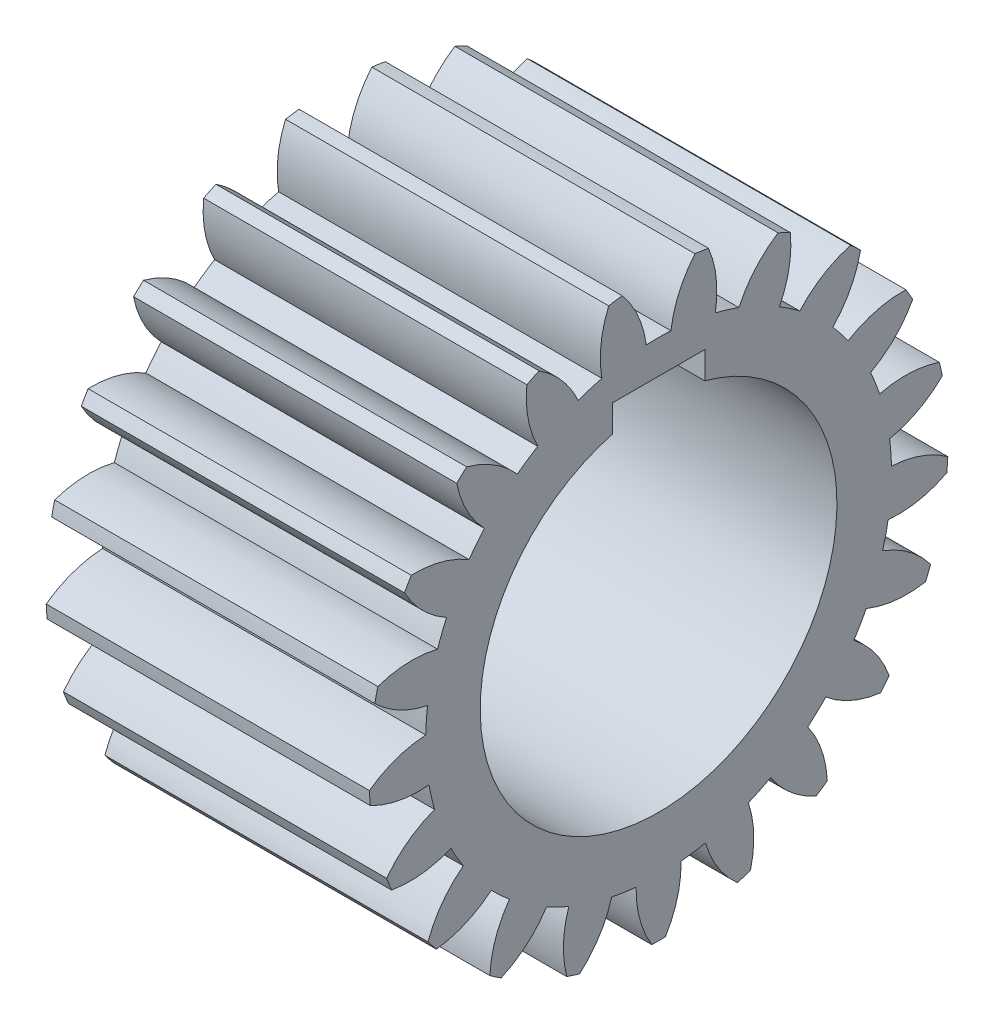
SolidWorks part; units mm, degrees
ref_plane "Plan de face" through (0, 0, 0) normal (0, 0, 1) x (1, 0, 0)
ref_plane "Plan de dessus" through (0, 0, 0) normal (0, 1, 0) x (1, 0, 0)
ref_plane "Plan de droite" through (0, 0, 0) normal (1, 0, 0) x (0, 0, -1)
ref_plane "Plan1" through (40.8214, 0, 0) normal (1, 0, 0) x (0, 0, -1)
sketch "Esquisse1" plane through (40.8214, 0, 0) normal (1, 0, 0) x (0, 0, -1)
  line L0 (-11, 30.2135) -> (11, 30.2135)
  line L1 (11, 30.2135) -> (11, 23.7653)
  line L2 (-11, 23.7653) -> (-11, 30.2135)
  arc A0 (11, 23.7653) -> (-11, 23.7653) centre (0, -17.2865) cw
  arc A1 (-67.6125, -3.5185) -> (-55.0464, -10.2132) centre (-49.9632, 14.4688) ccw
  arc A2 (-55.0464, -10.2132) -> (-55.4858, -16.0765) centre (0, -17.2865) ccw
  arc A3 (-55.4858, -16.0765) -> (-68.9093, -20.8235) centre (-54.138, -41.2404) ccw
  arc A4 (-68.9093, -20.8235) -> (-68.6668, -24.0593) centre (0, -17.2865) ccw
  arc A5 (-68.6668, -24.0593) -> (-54.6857, -26.7527) centre (-57.1035, -1.6689) ccw
  arc A6 (-54.6857, -26.7527) -> (-53.3774, -32.485) centre (0, -17.2865) ccw
  arc A7 (-53.3774, -32.485) -> (-64.8053, -40.9778) centre (-44.6723, -56.1337) ccw
  arc A8 (-64.8053, -40.9778) -> (-63.6198, -43.9983) centre (0, -17.2865) ccw
  arc A9 (-63.6198, -43.9983) -> (-49.466, -42.451) centre (-59.1699, -19.1943) ccw
  arc A10 (-49.466, -42.451) -> (-46.5261, -47.543) centre (0, -17.2865) ccw
  arc A11 (-46.5261, -47.543) -> (-54.943, -59.0269) centre (-31.2372, -67.5752) ccw
  arc A12 (-54.943, -59.0269) -> (-52.9199, -61.5638) centre (0, -17.2865) ccw
  arc A13 (-52.9199, -61.5638) -> (-39.851, -55.9134) centre (-55.9788, -36.5502) ccw
  arc A14 (-39.851, -55.9134) -> (-35.5408, -59.9126) centre (0, -17.2865) ccw
  arc A15 (-35.5408, -59.9126) -> (-40.1989, -73.3672) centre (-15.0266, -74.5483) ccw
  arc A16 (-40.1989, -73.3672) -> (-37.5178, -75.1951) centre (0, -17.2865) ccw
  arc A17 (-37.5178, -75.1951) -> (-26.695, -65.9436) centre (-47.8137, -52.1944) ccw
  arc A18 (-26.695, -65.9436) -> (-21.3976, -68.4947) centre (0, -17.2865) ccw
  arc A19 (-21.3976, -68.4947) -> (-21.8828, -82.7245) centre (2.5193, -76.4335) ccw
  arc A20 (-21.8828, -82.7245) -> (-18.7821, -83.681) centre (0, -17.2865) ccw
  arc A21 (-18.7821, -83.681) -> (-11.1671, -71.6504) centre (-35.4002, -64.7369) ccw
  arc A22 (-11.1671, -71.6504) -> (-5.3531, -72.5267) centre (0, -17.2865) ccw
  arc A23 (-5.3531, -72.5267) -> (-1.6224, -86.2674) centre (19.8412, -73.0632) ccw
  arc A24 (-1.6224, -86.2674) -> (1.6224, -86.2674) centre (0, -17.2865) ccw
  arc A25 (1.6224, -86.2674) -> (5.3531, -72.5267) centre (-19.8412, -73.0632) ccw
  arc A26 (5.3531, -72.5267) -> (11.1671, -71.6504) centre (0, -17.2865) ccw
  arc A27 (11.1671, -71.6504) -> (18.7821, -83.681) centre (35.4002, -64.7369) ccw
  arc A28 (18.7821, -83.681) -> (21.8828, -82.7245) centre (0, -17.2865) ccw
  arc A29 (21.8828, -82.7245) -> (21.3976, -68.4947) centre (-2.5193, -76.4335) ccw
  arc A30 (21.3976, -68.4947) -> (26.695, -65.9436) centre (0, -17.2865) ccw
  arc A31 (26.695, -65.9436) -> (37.5178, -75.1951) centre (47.8137, -52.1944) ccw
  arc A32 (37.5178, -75.1951) -> (40.1989, -73.3672) centre (0, -17.2865) ccw
  arc A33 (40.1989, -73.3672) -> (35.5408, -59.9126) centre (15.0266, -74.5483) ccw
  arc A34 (35.5408, -59.9126) -> (39.851, -55.9134) centre (0, -17.2865) ccw
  arc A35 (39.851, -55.9134) -> (52.9199, -61.5638) centre (55.9788, -36.5502) ccw
  arc A36 (52.9199, -61.5638) -> (54.943, -59.0269) centre (0, -17.2865) ccw
  arc A37 (54.943, -59.0269) -> (46.5261, -47.543) centre (31.2372, -67.5752) ccw
  arc A38 (46.5261, -47.543) -> (49.466, -42.451) centre (0, -17.2865) ccw
  arc A39 (49.466, -42.451) -> (63.6198, -43.9983) centre (59.1699, -19.1943) ccw
  arc A40 (63.6198, -43.9983) -> (64.8053, -40.9778) centre (0, -17.2865) ccw
  arc A41 (64.8053, -40.9778) -> (53.3774, -32.485) centre (44.6723, -56.1337) ccw
  arc A42 (53.3774, -32.485) -> (54.6857, -26.7527) centre (0, -17.2865) ccw
  arc A43 (54.6857, -26.7527) -> (68.6668, -24.0593) centre (57.1035, -1.6689) ccw
  arc A44 (68.6668, -24.0593) -> (68.9093, -20.8235) centre (0, -17.2865) ccw
  arc A45 (68.9093, -20.8235) -> (55.4858, -16.0765) centre (54.138, -41.2404) ccw
  arc A46 (55.4858, -16.0765) -> (55.0464, -10.2132) centre (0, -17.2865) ccw
  arc A47 (55.0464, -10.2132) -> (67.6125, -3.5185) centre (49.9632, 14.4688) ccw
  arc A48 (67.6125, -3.5185) -> (66.8904, -0.355) centre (0, -17.2865) ccw
  arc A49 (66.8904, -0.355) -> (52.6641, 0.2245) centre (58.7934, -24.2188) ccw
  arc A50 (52.6641, 0.2245) -> (50.516, 5.6978) centre (0, -17.2865) ccw
  arc A51 (50.516, 5.6978) -> (60.5505, 15.7989) centre (38.3834, 27.7849) ccw
  arc A52 (60.5505, 15.7989) -> (58.928, 18.6091) centre (0, -17.2865) ccw
  arc A53 (58.928, 18.6091) -> (45.1629, 14.9695) centre (58.2247, -6.5811) ccw
  arc A54 (45.1629, 14.9695) -> (41.497, 19.5665) centre (0, -17.2865) ccw
  arc A55 (41.497, 19.5665) -> (48.1083, 32.1766) centre (23.3932, 37.0962) ccw
  arc A56 (48.1083, 32.1766) -> (45.7296, 34.3837) centre (0, -17.2865) ccw
  arc A57 (45.7296, 34.3837) -> (33.6488, 26.8485) centre (52.4824, 10.1053) ccw
  arc A58 (33.6488, 26.8485) -> (28.7908, 30.1606) centre (0, -17.2865) ccw
  arc A59 (28.7908, 30.1606) -> (31.3915, 44.1592) centre (6.3243, 41.5754) ccw
  arc A60 (31.3915, 44.1592) -> (28.4679, 45.5671) centre (0, -17.2865) ccw
  arc A61 (28.4679, 45.5671) -> (19.1449, 34.8059) centre (42.0769, 24.3578) ccw
  arc A62 (19.1449, 34.8059) -> (13.5264, 36.5389) centre (0, -17.2865) ccw
  arc A63 (13.5264, 36.5389) -> (11.8854, 50.6822) centre (-11.3065, 40.8244) ccw
  arc A64 (11.8854, 50.6822) -> (8.6768, 51.1658) centre (0, -17.2865) ccw
  arc A65 (8.6768, 51.1658) -> (2.9399, 38.1346) centre (27.9327, 34.9101) ccw
  arc A66 (2.9399, 38.1346) -> (-2.9399, 38.1346) centre (0, -17.2865) ccw
  arc A67 (-2.9399, 38.1346) -> (-8.6768, 51.1658) centre (-27.9327, 34.9101) ccw
  arc A68 (-8.6768, 51.1658) -> (-11.8854, 50.6822) centre (0, -17.2865) ccw
  arc A69 (-11.8854, 50.6822) -> (-13.5264, 36.5389) centre (11.3065, 40.8244) ccw
  arc A70 (-13.5264, 36.5389) -> (-19.1449, 34.8059) centre (0, -17.2865) ccw
  arc A71 (-19.1449, 34.8059) -> (-28.4679, 45.5671) centre (-42.0769, 24.3578) ccw
  arc A72 (-28.4679, 45.5671) -> (-31.3915, 44.1592) centre (0, -17.2865) ccw
  arc A73 (-31.3915, 44.1592) -> (-28.7908, 30.1606) centre (-6.3243, 41.5754) ccw
  arc A74 (-28.7908, 30.1606) -> (-33.6488, 26.8485) centre (0, -17.2865) ccw
  arc A75 (-33.6488, 26.8485) -> (-45.7296, 34.3837) centre (-52.4824, 10.1053) ccw
  arc A76 (-45.7296, 34.3837) -> (-48.1083, 32.1766) centre (0, -17.2865) ccw
  arc A77 (-48.1083, 32.1766) -> (-41.497, 19.5665) centre (-23.3932, 37.0962) ccw
  arc A78 (-41.497, 19.5665) -> (-45.1629, 14.9695) centre (0, -17.2865) ccw
  arc A79 (-45.1629, 14.9695) -> (-58.928, 18.6091) centre (-58.2247, -6.5811) ccw
  arc A80 (-58.928, 18.6091) -> (-60.5505, 15.7989) centre (0, -17.2865) ccw
  arc A81 (-60.5505, 15.7989) -> (-50.516, 5.6978) centre (-38.3834, 27.7849) ccw
  arc A82 (-50.516, 5.6978) -> (-52.6641, 0.2245) centre (0, -17.2865) ccw
  arc A83 (-52.6641, 0.2245) -> (-66.8904, -0.355) centre (-58.7934, -24.2188) ccw
  arc A84 (-66.8904, -0.355) -> (-67.6125, -3.5185) centre (0, -17.2865) ccw
extrude "Boss.-Extru.1" add sketch "Esquisse1" against normal blind 77
